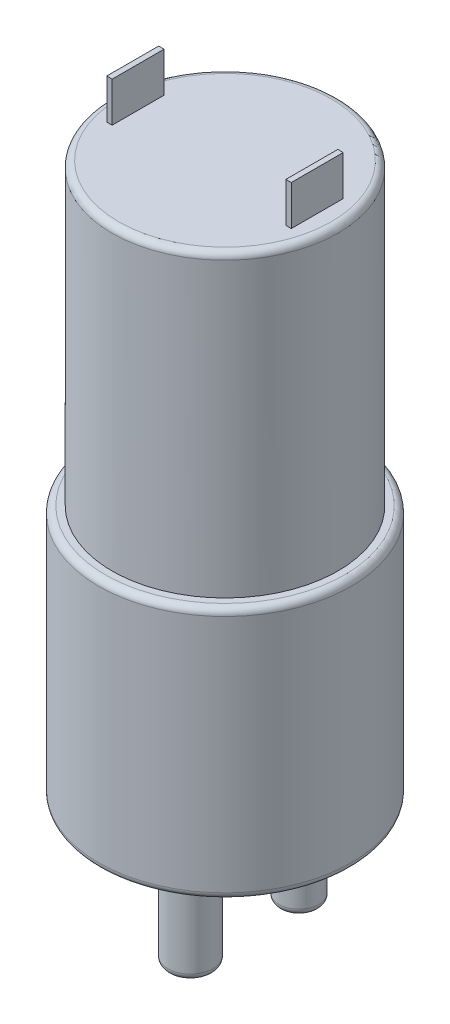
SolidWorks part; units mm, degrees
material "6061 合金"
ref_plane "前视基准面" through (0, 0, 0) normal (0, 0, 1) x (1, 0, 0)
ref_plane "上视基准面" through (0, 0, 0) normal (0, 1, 0) x (1, 0, 0)
ref_plane "右视基准面" through (0, 0, 0) normal (1, 0, 0) x (0, 0, -1)
other "Configuration Table"
sketch "草图1" plane through (0, 0, 0) normal (0, 1, 0) x (1, 0, 0)
  circle A0 centre (0, 0) radius 8.5
  dimension "D1" = 17
extrude "凸台-拉伸1" add sketch "草图1" along normal blind 22.5
sketch "草图2" plane through (0, 0, 0) normal (0, -1, 0) x (1, 0, 0)
  circle A2 centre (0, 0) radius 9.5
  circle A3 centre (0, 0) radius 9.5
  dimension "D1" = 1
extrude "凸台-拉伸2" add sketch "草图2" along normal blind 19
sketch "草图3" plane through (0, -19, 0) normal (0, -1, 0) x (1, 0, 0)
  line L0 (0, 4.3) -> (3.7645, 4.3) construction
  line L1 (0, 9.5) -> (4.1918, 9.5) construction
  line L2 (0, -3.7645) -> (0, 2.6) construction
  circle A0 centre (0, 2.6) radius 1.7
  circle A1 centre (0, 2.6) radius 0.2
  circle A4 centre (0, -5.5639) radius 1.5
  circle A5 centre (0, -5.5639) radius 0.1
  point P13 (0, 0)
  point P15 (0, -4.3117)
  dimension "D1" = 5.2
extrude "凸台-拉伸3" add sketch "草图3" along normal blind 9.5
sketch "草图4" plane through (0, 22.5, 0) normal (0, 1, 0) x (1, 0, 0)
  line L0 (0, 0) -> (16.9096, 0) construction
  line L1 (0, 0) -> (0, 5.3923) construction
  line L2 (-6.9388, -1.9535) -> (-6.5319, -1.9535)
  line L3 (-6.9388, -1.9535) -> (-6.9388, 1.9535)
  line L4 (-6.9388, 1.9535) -> (-6.5319, 1.9535)
  line L5 (-6.5319, -1.9535) -> (-6.5319, 1.9535)
  line L6 (-6.9388, -1.9535) -> (-6.5319, 1.9535) construction
  line L7 (-6.9388, 1.9535) -> (-6.5319, -1.9535) construction
  line L8 (6.9388, 1.9535) -> (6.5319, -1.9535) construction
  line L9 (6.9388, -1.9535) -> (6.5319, 1.9535) construction
  line L10 (6.5319, -1.9535) -> (6.5319, 1.9535)
  line L11 (6.9388, 1.9535) -> (6.5319, 1.9535)
  line L12 (6.9388, -1.9535) -> (6.9388, 1.9535)
  line L13 (6.9388, -1.9535) -> (6.5319, -1.9535)
  point P1 (-6.7353, 0)
  point P15 (6.7353, 0)
extrude "凸台-拉伸4" add sketch "草图4" along normal blind 3
fillet "圆角2" radius 0.5 7 edges at (0, -19, -7.0639) (0, -19, 0.9) (0, -28.5, 0.9) (0, -28.5, -7.0639) (0, -19, -9.5) (0, 0, -9.5) (0, 22.5, 8.5)
